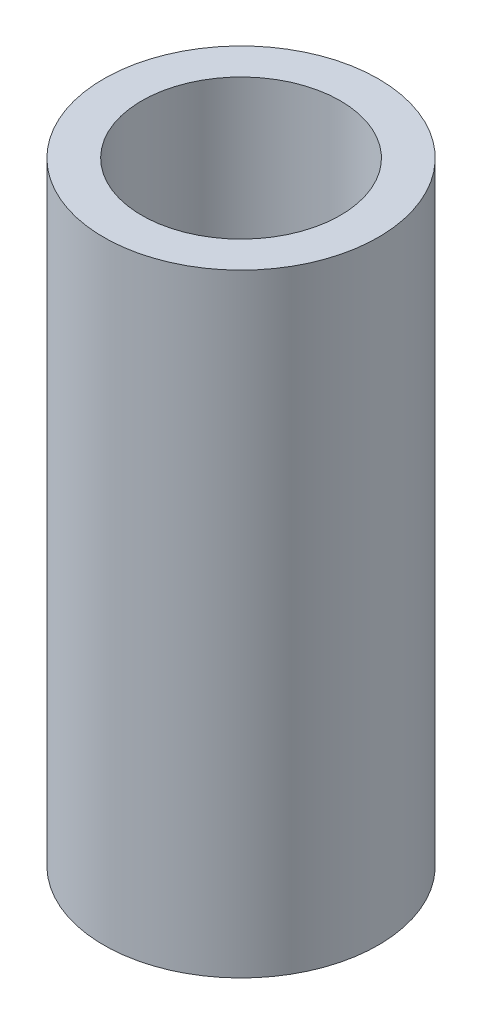
SolidWorks part; units mm, degrees
ref_plane "Front Plane" through (0, 0, 0) normal (0, 0, 1) x (1, 0, 0)
ref_plane "Top Plane" through (0, 0, 0) normal (0, 1, 0) x (1, 0, 0)
ref_plane "Right Plane" through (0, 0, 0) normal (1, 0, 0) x (0, 0, -1)
sketch "Sketch1" plane through (0, 0, 0) normal (0, 0, 1) x (1, 0, 0)
  line L0 (0, 0) -> (0, 31.1949) construction
  line L2 (4.05, 0) -> (5.6, 0)
  line L3 (4.05, 0) -> (4.05, 25)
  line L4 (4.05, 25) -> (5.6, 25)
  line L5 (5.6, 0) -> (5.6, 25)
  dimension "D1" = 8.1
  dimension "D2" = 11.2
  dimension "D3" = 25
revolve "Revolve1" add sketch "Sketch1" angle 360 about L0
